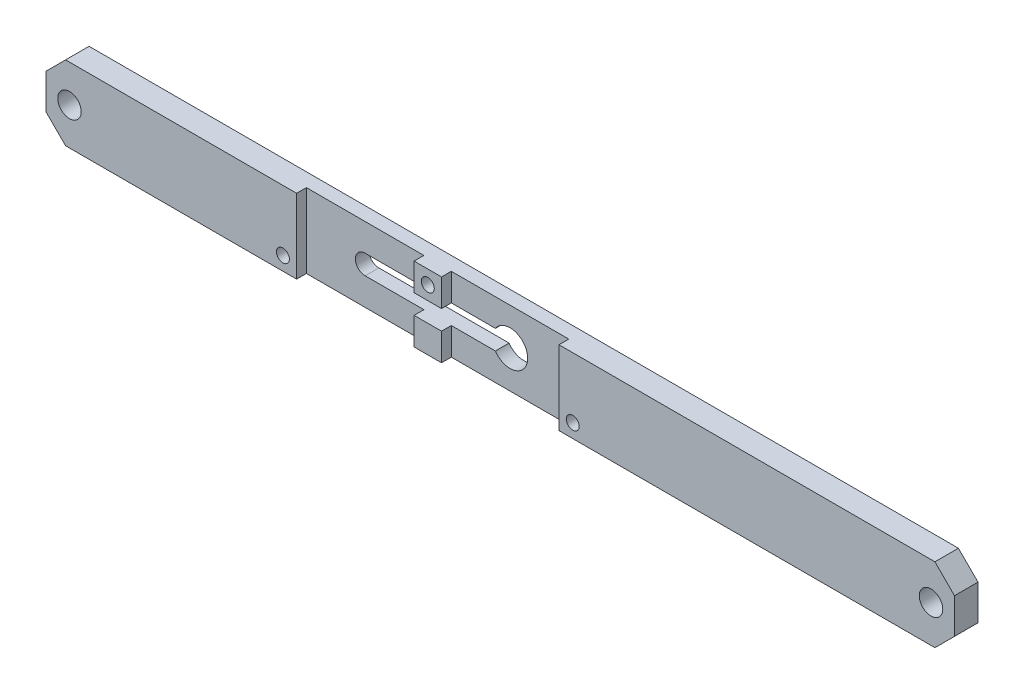
SolidWorks part; units mm, degrees
ref_plane "前视基准面" through (0, 0, 0) normal (0, 0, 1) x (1, 0, 0)
ref_plane "上视基准面" through (0, 0, 0) normal (0, 1, 0) x (1, 0, 0)
ref_plane "右视基准面" through (0, 0, 0) normal (1, 0, 0) x (0, 0, -1)
sketch "草图1" plane through (0, 0, 0) normal (0, 0, 1) x (1, 0, 0)
  line L1 (116, -9.5) -> (-116, -9.5)
  line L2 (116, -9.5) -> (116, 9.5)
  line L3 (116, 9.5) -> (-116, 9.5)
  line L4 (-116, -9.5) -> (-116, 9.5)
  line L5 (116, -9.5) -> (-116, 9.5) construction
  line L6 (116, 9.5) -> (-116, -9.5) construction
  point P0 (0, 0)
  dimension "D1" = 19
  dimension "D2" = 232
extrude "凸台-拉伸1" add sketch "草图1" along normal blind 6
sketch "草图3" plane through (0, 0, 6) normal (0, 0, 1) x (1, 0, 0)
  line L0 (116, 9.5) -> (-116, 9.5) construction
  line L1 (-52, 9.5) -> (-22, 9.5)
  line L2 (-52, 9.5) -> (-52, -9.5)
  line L3 (-52, -9.5) -> (-22, -9.5)
  line L4 (-22, 9.5) -> (-22, -9.5)
  line L5 (-116, -9.5) -> (116, -9.5) construction
  line L6 (-116, 9.5) -> (-116, -9.5) construction
  line L7 (-15, 9.5) -> (-15, -9.5)
  line L8 (-15, 9.5) -> (15, 9.5)
  line L9 (15, 9.5) -> (15, -9.5)
  line L10 (-15, -9.5) -> (15, -9.5)
  dimension "D1" = 64
  dimension "D2" = 30
  dimension "D4" = 7
  dimension "D3" = 2
extrude "切除-拉伸2" cut sketch "草图3" against normal blind 2.5
sketch "草图5" plane through (0, 0, 6) normal (0, 0, 1) x (1, 0, 0)
  line L0 (-15, 0) -> (-22, 0) construction
  line L1 (-15, 9.5) -> (-15, -9.5) construction
  line L2 (-22, -9.5) -> (-22, 9.5) construction
  line L3 (-18.5, 0) -> (-18.5, 50000) construction
  line L4 (-116, 9.5) -> (-116, -9.5) construction
  line L5 (116, -9.5) -> (116, 9.5) construction
  circle A0 centre (110, 0) radius 3
  circle A1 centre (-110, 0) radius 3
  point P12 (-18.5, 0)
  point P15 (-110, -1.8511)
  dimension "D1" = 6
  dimension "D2" = 6
  dimension "D3" = 6
extrude "切除-拉伸4" cut sketch "草图5" against normal through all
sketch "草图4" plane through (0, 0, 6) normal (0, 0, 1) x (1, 0, 0)
  line L0 (-37, 0) -> (0, 0) construction
  line L1 (-37, 2.5) -> (0, 2.5)
  line L2 (-37, -2.5) -> (0, -2.5)
  circle A0 centre (0, 0) radius 4.5
  arc A1 (-37, 2.5) -> (-37, -2.5) centre (-37, 0) ccw
  arc A2 (0, -2.5) -> (0, 2.5) centre (0, 0) ccw
  circle A3 centre (110, 0) radius 3 construction
  point P4 (-18.5, 0)
  point P10 (-25.8334, 0)
  point P11 (-40.2086, 0)
  dimension "D1" = 9
  dimension "D3" = 110
  dimension "D4" = 2.5
  dimension "D2" = 37
extrude "切除-拉伸3" cut sketch "草图4" against normal through all
chamfer "倒角1" distance 5 angle 45 4 edges at (116, -9.5, 3) (116, 9.5, 3) (-116, 9.5, 3) (-116, -9.5, 3)
sketch "草图6" plane through (0, 0, 0) normal (0, 0, 1) x (1, 0, 0)
  line L0 (-18.5, -2.5) -> (-18.5, 20.8098) construction
  line L1 (-22, -2.5) -> (-15, -2.5) construction
  circle A0 centre (-18.5, 6) radius 2.5
  circle A1 centre (-55.5, -6) radius 2.5
  circle A2 centre (18.5, -6) radius 2.5
  circle A3 centre (-110, 0) radius 3 construction
  point P0 (-18.5, 6)
  point P2 (-55.5, -6)
  point P4 (18.5, -6)
  dimension "D1" = 5
  dimension "D2" = 37
  dimension "D3" = 37
  dimension "D4" = 6
  dimension "D5" = 6
hole_wizard "M6 内六角花形半沉头螺钉的锥形沉头孔1" positions "草图6" profile "草图7" countersink size "M6" standard "GB" end condition through all
sketch "草图7" plane through (-18.5, 6, 0) normal (1, 0, 0) x (0, 1, 0)
  line L0 (0, 0) -> (0, 6)
  line L1 (0, 6) -> (1.65, 6)
  line L2 (1.65, 6) -> (1.65, 1.35)
  line L3 (1.65, 1.35) -> (3, 0)
  line L5 (3, 0) -> (0, 0)
  line L6 (-1.65, 1.35) -> (-3, 0) construction
  line L11 (0, -6.35) -> (0, 107.95) construction
  dimension "通孔孔直径" = 3.3
  dimension "通孔孔深度" = 6
  dimension "近端锥形沉头孔直径" = 6
  dimension "近端锥形沉头孔角度" = 90
